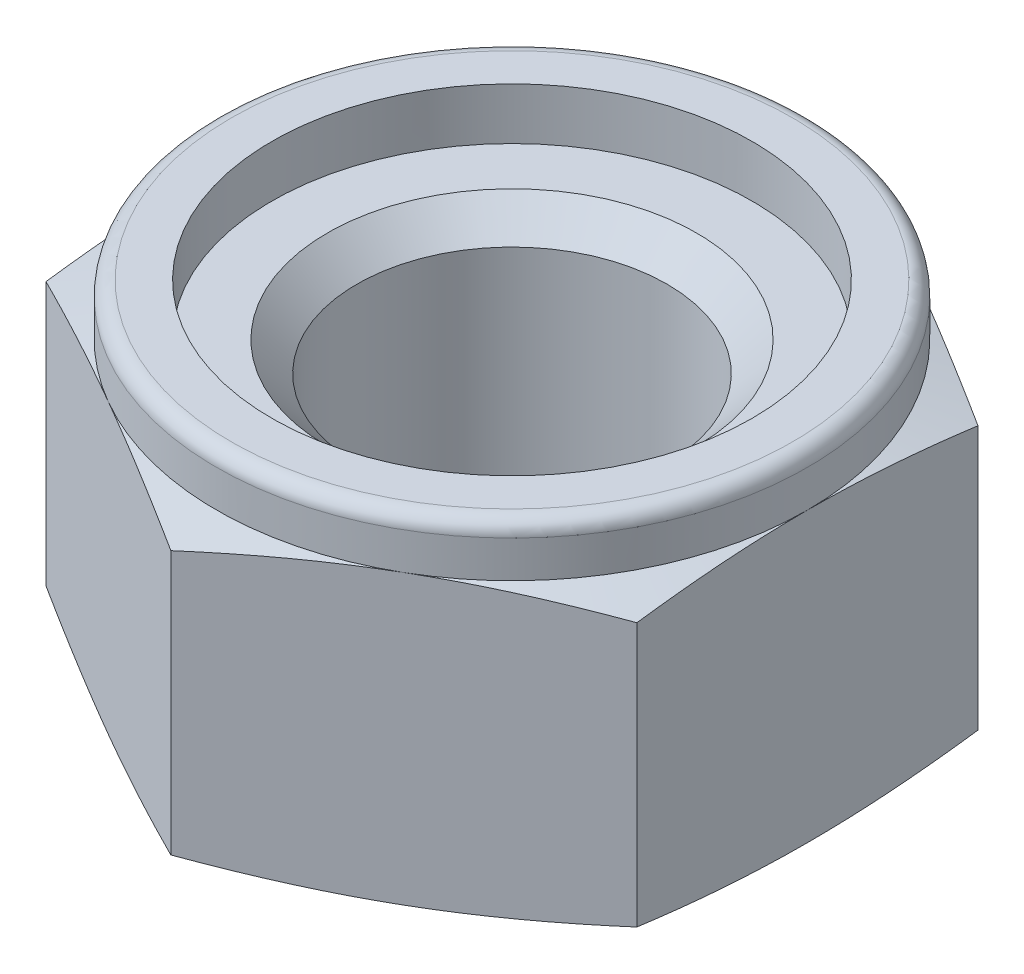
SolidWorks part; units mm, degrees
ref_plane "Front Plane" through (0, 0, 0) normal (0, 0, 1) x (1, 0, 0)
ref_plane "Top Plane" through (0, 0, 0) normal (0, 1, 0) x (1, 0, 0)
ref_plane "Right Plane" through (0, 0, 0) normal (1, 0, 0) x (0, 0, -1)
sketch "Sketch1" plane through (0, 0, 0) normal (0, 1, 0) x (1, 0, 0)
  line L1 (0, 4.6188) -> (-4, 2.3094)
  line L2 (-4, 2.3094) -> (-4, -2.3094)
  line L3 (-4, -2.3094) -> (0, -4.6188)
  line L4 (0, -4.6188) -> (4, -2.3094)
  line L5 (4, -2.3094) -> (4, 2.3094)
  line L6 (4, 2.3094) -> (0, 4.6188)
  circle A0 centre (0, 0) radius 4 construction
  dimension "UNT_S" = 8
extrude "Boss-Extrude1" add sketch "Sketch1" against normal blind 3.9
sketch "Sketch2" plane through (0, 0, 0) normal (1, 0, 0) x (0, 0, -1)
  line L0 (0, 0) -> (0, -3.9) construction
  line L1 (-2.3094, -3.9) -> (2.3094, -3.9) construction
  line L2 (4, 0) -> (4.6188, 0)
  line L3 (4.6188, 0) -> (4.6188, -0.1658)
  line L4 (4.6188, -0.1658) -> (4, 0)
  line L5 (2.3094, 0) -> (4.6188, 0) construction
  line L6 (4.6188, -3.9) -> (4.6188, 0) construction
  line L7 (2.3094, -3.9) -> (4.6188, -3.9) construction
  line L8 (4.6188, -3.7342) -> (4, -3.9)
  line L9 (4.6188, -3.9) -> (4.6188, -3.7342)
  line L10 (4, -3.9) -> (4.6188, -3.9)
  dimension "D1" = 15
revolve "Cut-Revolve1" cut sketch "Sketch2" angle 360 about L0
hole_wizard "Tapped Hole1" positions "Sketch4" profile "Sketch3" tap size "M5x0.8" standard "JIS" end condition through all
sketch "Sketch4" plane through (0, 0, 0) normal (0, 1, 0) x (1, 0, 0)
  point P0 (0, 0)
sketch "Sketch3" plane through (0, 0, 0) normal (1, 0, 0) x (0, 0, 1)
  line L0 (0, 0) -> (0, 3.9)
  line L1 (0, 3.9) -> (2.1, 3.9)
  line L2 (2.1, 3.9) -> (2.1, 0)
  line L5 (2.1, 0) -> (0, 0)
  line L11 (0, 0) -> (0, 3.9) construction
  dimension "Thru Tap Drill Dia." = 4.2
  dimension "Thru Tap Drill Depth" = 3.9
cosmetic thread "Hole Thread1" parameters "UNT_M"=5
chamfer "Chamfer1" distance 0.4 angle 45 2 edges at (0, -3.9, 2.1) (0, 0, 2.1)
sketch "Sketch5" plane through (0, 0, 0) normal (0, 0, 1) x (1, 0, 0)
  line L0 (4, 0) -> (4, 0.7)
  line L1 (4, 0.7) -> (3.25, 0.7)
  line L2 (4, 0) -> (2, 0) construction
  line L3 (4, 0) -> (3.25, 0)
  line L4 (-2, -3.9) -> (2, -3.9) construction
  line L5 (3.25, 0.7) -> (3.25, 0)
  line L6 (4, -3.7342) -> (4, -0.1658) construction
  line L8 (2, 0) -> (-2, 0) construction
  line L9 (0, 0) -> (0, 0.7) construction
  dimension "UNT_H_s" = 4.6
  dimension "UNT_MSM_1" = 6.5
revolve "Revolve1" add sketch "Sketch5" angle 360 about L9
fillet "Fillet1" radius 0.2 1 edges at (4, 0.7, 0)
